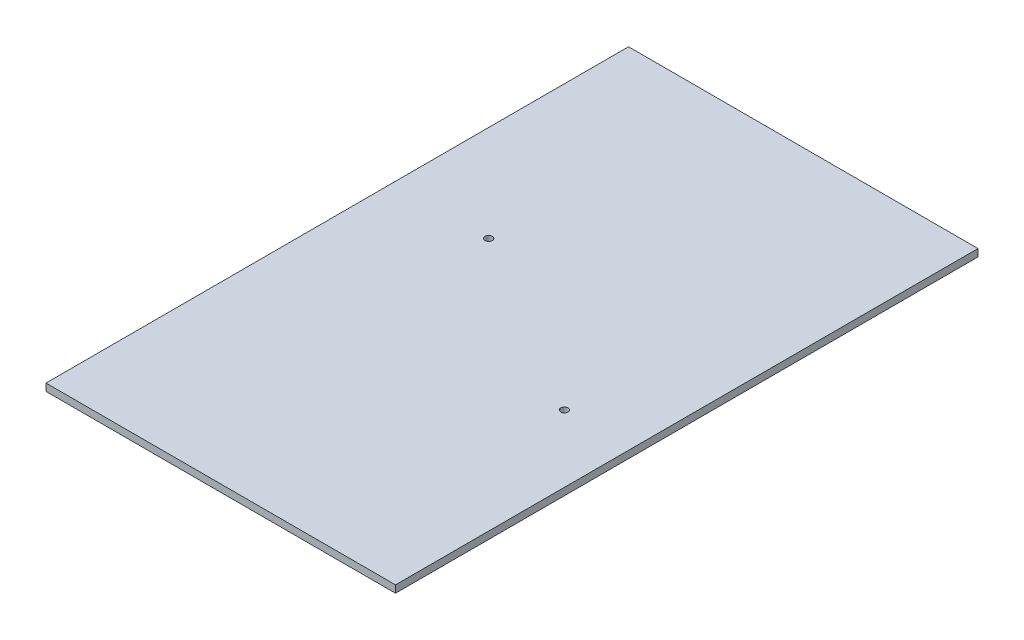
SolidWorks part; units mm, degrees
ref_plane "Front Plane" through (0, 0, 0) normal (0, 0, 1) x (1, 0, 0)
ref_plane "Top Plane" through (0, 0, 0) normal (0, 1, 0) x (1, 0, 0)
ref_plane "Right Plane" through (0, 0, 0) normal (1, 0, 0) x (0, 0, -1)
sketch "Sketch1" plane through (0, 0, 0) normal (0, 1, 0) x (1, 0, 0)
  line L1 (-76.2, -127) -> (76.2, -127)
  line L2 (-76.2, -127) -> (-76.2, 127)
  line L3 (-76.2, 127) -> (76.2, 127)
  line L4 (76.2, -127) -> (76.2, 127)
  line L5 (-76.2, -127) -> (76.2, 127) construction
  line L6 (-76.2, 127) -> (76.2, -127) construction
  point P0 (0, 0)
  dimension "D1" = 254
  dimension "D2" = 152.4
extrude "Boss-Extrude1" add sketch "Sketch1" along normal blind 3.175
sketch "Sketch4" plane through (0, 3.175, 0) normal (0, 1, 0) x (1, 0, 0)
  circle A0 centre (-34.29, 24.13) radius 1.5875
  circle A1 centre (46.99, -24.13) radius 1.5875
  dimension "D5" = 3.175
  dimension "D6" = 3.175
  dimension "D1" = 24.13
  dimension "D2" = 34.29
  dimension "D3" = 81.28
  dimension "D4" = 48.26
extrude "Cut-Extrude1" cut sketch "Sketch4" against normal through all
equation "\"R_megaHole\"= 0.125in"
equation "\"X_megaHoleDist\"= 3.2in'Hole distances from each other"
equation "\"Z_megaHoleDist\"= 1.9in"
equation "\"X_megaHoleO\"= 1.35in'Hole 1 distance from origin"
equation "\"Z_megaHoleO\"= 0.95in"
equation "\"D2@Sketch4\"= \"X_megaHoleO\""
equation "\"D1@Sketch4\"= \"Z_megaHoleO\""
equation "\"D3@Sketch4\"= \"X_megaHoleDist\""
equation "\"D4@Sketch4\"= \"Z_megaHoleDist\""
equation "\"D6@Sketch4\"= \"R_megaHole\""
equation "\"D5@Sketch4\"= \"R_megaHole\""
